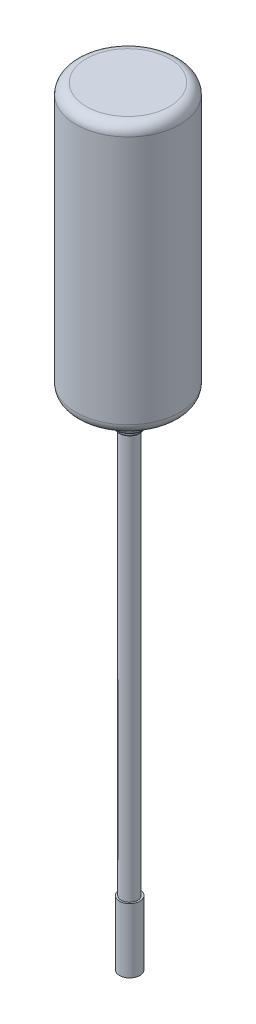
SolidWorks part; units mm, degrees
ref_plane "Front Plane" through (0, 0, 0) normal (0, 0, 1) x (1, 0, 0)
ref_plane "Top Plane" through (0, 0, 0) normal (0, 1, 0) x (1, 0, 0)
ref_plane "Right Plane" through (0, 0, 0) normal (1, 0, 0) x (0, 0, -1)
sketch "Sketch1" plane through (0, 0, 0) normal (0, 1, 0) x (1, 0, 0)
  circle A0 centre (-177.9631, -16.9065) radius 25
  dimension "D1" = 50
extrude "Boss-Extrude1" add sketch "Sketch1" against normal blind 130
sketch "Sketch2" plane through (0, -130, 0) normal (0, -1, 0) x (1, 0, 0)
  circle A0 centre (-177.6739, 16.4598) radius 4
extrude "Boss-Extrude2" add sketch "Sketch2" along normal blind 240 contours A0
fillet "Fillet1" radius 5 2 edges at (-177.9631, 0, 41.9065) (-177.9631, -130, 41.9065)
sketch "Sketch3" plane through (0, -370, 0) normal (0, -1, 0) x (1, 0, 0)
  circle A0 centre (-177.6968, 16.5293) radius 1.4539
extrude "Boss-Extrude3" add sketch "Sketch3" against normal blind 11
sketch "Sketch4" plane through (0, -130, 0) normal (0, -1, 0) x (1, 0, 0)
  circle A0 centre (-177.6824, 16.3686) radius 8
sketch "Sketch5" plane through (0, -370, 0) normal (0, -1, 0) x (1, 0, 0)
  circle A0 centre (-177.6824, 16.3686) radius 4.874
extrude "Boss-Extrude4" add sketch "Sketch5" against normal blind 31
extrude "Boss-Extrude5" add sketch "Sketch4" along normal blind 6
sketch "Sketch6" plane through (0, -136, 0) normal (0, -1, 0) x (1, 0, 0)
  circle A0 centre (-177.6739, 16.4598) radius 6.0081
extrude "Boss-Extrude6" add sketch "Sketch6" along normal blind 3
sketch "Sketch7" plane through (0, -139, 0) normal (0, -1, 0) x (1, 0, 0)
  circle A0 centre (-177.6824, 16.3686) radius 7
extrude "Boss-Extrude7" add sketch "Sketch7" along normal blind 3
sketch "Sketch8" plane through (0, -142, 0) normal (0, -1, 0) x (1, 0, 0)
  circle A0 centre (-177.6739, 16.4598) radius 5.1204
extrude "Boss-Extrude8" add sketch "Sketch8" along normal blind 2
fillet "Fillet2" radius 1 2 edges at (-177.6824, -142, 9.3686) (-177.6824, -136, 8.3686)
fillet "Fillet3" radius 0.7 1 edges at (-177.6739, -139, 10.4517)
fillet "Fillet4" radius 0.5 1 edges at (-177.6739, -144, 11.3395)
